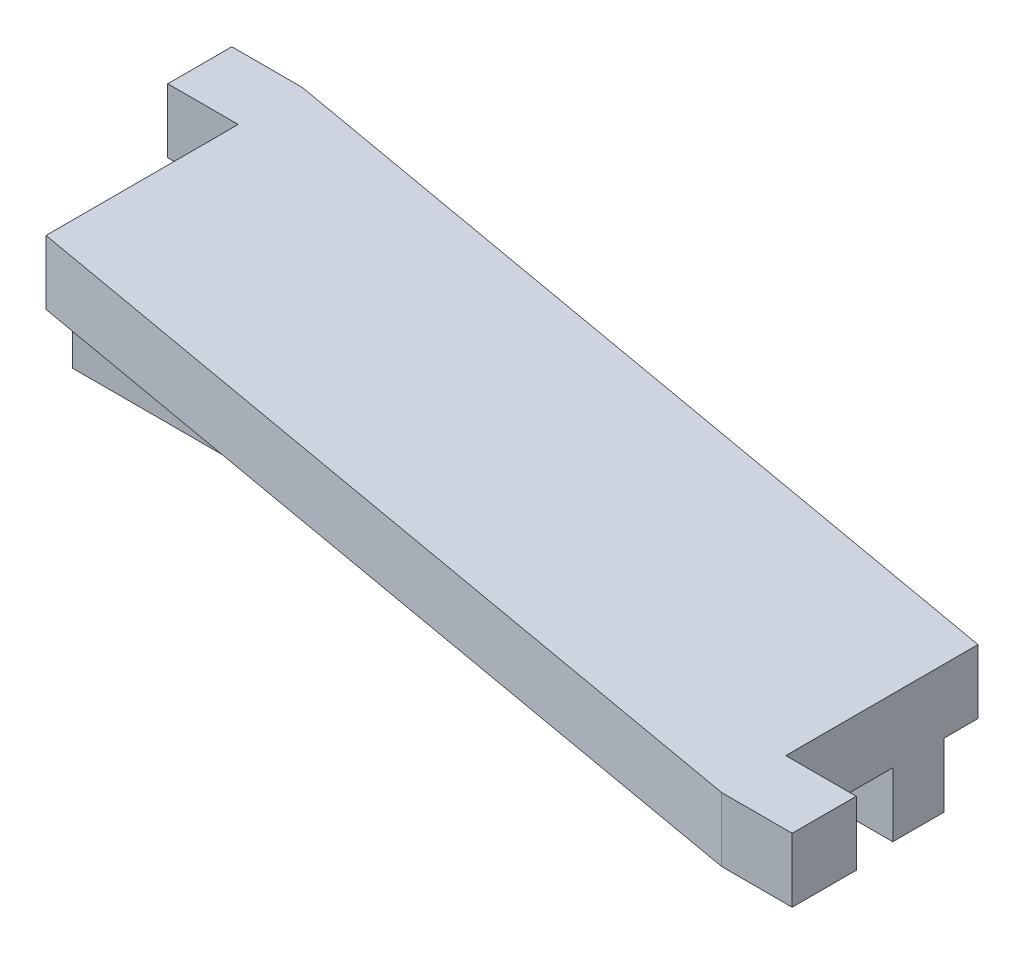
SolidWorks part; units mm, degrees
ref_plane "Front Plane" through (0, 0, 0) normal (0, 0, 1) x (1, 0, 0)
ref_plane "Top Plane" through (0, 0, 0) normal (0, 1, 0) x (1, 0, 0)
ref_plane "Right Plane" through (0, 0, 0) normal (1, 0, 0) x (0, 0, -1)
sketch "Sketch1" plane through (0, 0, 0) normal (0, 1, 0) x (1, 0, 0)
  line L0 (0, 0) -> (-128.025, 22.5743)
  line L1 (0, 0) -> (-98.5093, 0) construction
  line L2 (-128.025, 22.5743) -> (-128.025, 52.5743)
  line L3 (-128.025, 52.5743) -> (-139.025, 52.5743)
  line L4 (-139.025, 52.5743) -> (-139.025, 62.5743)
  line L5 (-139.025, 62.5743) -> (-128.025, 62.5743)
  line L6 (0, 40) -> (0, 10)
  line L7 (0, 10) -> (11, 10)
  line L8 (11, 10) -> (11, 0)
  line L9 (11, 0) -> (0, 0)
  line L10 (-128.025, 62.5743) -> (0, 40)
  dimension "D1" = 10
  dimension "D2" = 130
  dimension "D3" = 10
  dimension "D4" = 30
  dimension "D5" = 11
  dimension "D6" = 11
extrude "Boss-Extrude1" add sketch "Sketch1" along normal blind 10
sketch "Sketch2" plane through (0, 0, 0) normal (0, -1, 0) x (1, 0, 0)
  line L0 (0, -40) -> (-128.025, -37.5743)
  line L1 (-128.025, -52.5743) -> (-128.025, -22.5743) construction
  line L2 (-128.025, -37.5743) -> (-128.025, -32)
  line L3 (-128.025, -32) -> (0, -32)
  line L6 (0, -10) -> (0, -40) construction
  line L7 (0, -32) -> (0, -40)
  dimension "D1" = 8
extrude "Boss-Extrude2" [suppressed] add sketch "Sketch2" along normal blind 10
sketch "Sketch5" plane through (0, 10, 0) normal (0, 1, 0) x (1, 0, 0)
  line L0 (8.5, 10) -> (6.4527, 4.375)
  line L1 (11, 10) -> (0, 10) construction
  line L2 (6.4527, 4.375) -> (4.2785, 4.375)
  line L3 (4.2785, 4.375) -> (2.2311, 10)
  line L4 (6.4527, 4.375) -> (6.4527, 23.9951) construction
  line L5 (3.1411, 7.5) -> (7.5901, 7.5) construction
  line L6 (0, 0) -> (11, 0) construction
  line L7 (2.2311, 10) -> (8.5, 10)
  line L8 (-5.5377, 10) -> (0.7311, 10)
  line L9 (0.7311, 10) -> (-1.3162, 4.375)
  line L10 (-1.3162, 4.375) -> (-3.4904, 4.375)
  line L11 (-3.4904, 4.375) -> (-5.5377, 10)
  line L12 (-13.3066, 10) -> (-7.0377, 10)
  line L13 (-7.0377, 10) -> (-9.085, 4.375)
  line L14 (-9.085, 4.375) -> (-11.2592, 4.375)
  line L15 (-11.2592, 4.375) -> (-13.3066, 10)
  line L16 (-21.0754, 10) -> (-14.8066, 10)
  line L17 (-14.8066, 10) -> (-16.8539, 4.375)
  line L18 (-16.8539, 4.375) -> (-19.0281, 4.375)
  line L19 (-19.0281, 4.375) -> (-21.0754, 10)
  line L20 (-28.8443, 10) -> (-22.5754, 10)
  line L21 (-22.5754, 10) -> (-24.6227, 4.375)
  line L22 (-24.6227, 4.375) -> (-26.7969, 4.375)
  line L23 (-26.7969, 4.375) -> (-28.8443, 10)
  line L24 (-36.6131, 10) -> (-30.3443, 10)
  line L25 (-30.3443, 10) -> (-32.3916, 4.375)
  line L26 (-32.3916, 4.375) -> (-34.5658, 4.375)
  line L27 (-34.5658, 4.375) -> (-36.6131, 10)
  line L28 (-44.382, 10) -> (-38.1131, 10)
  line L29 (-38.1131, 10) -> (-40.1604, 4.375)
  line L30 (-40.1604, 4.375) -> (-42.3346, 4.375)
  line L31 (-42.3346, 4.375) -> (-44.382, 10)
  line L32 (-52.1508, 10) -> (-45.882, 10)
  line L33 (-45.882, 10) -> (-47.9293, 4.375)
  line L34 (-47.9293, 4.375) -> (-50.1035, 4.375)
  line L35 (-50.1035, 4.375) -> (-52.1508, 10)
  line L36 (-59.9197, 10) -> (-53.6508, 10)
  line L37 (-53.6508, 10) -> (-55.6981, 4.375)
  line L38 (-55.6981, 4.375) -> (-57.8723, 4.375)
  line L39 (-57.8723, 4.375) -> (-59.9197, 10)
  line L40 (-67.6885, 10) -> (-61.4197, 10)
  line L41 (-61.4197, 10) -> (-63.467, 4.375)
  line L42 (-63.467, 4.375) -> (-65.6412, 4.375)
  line L43 (-65.6412, 4.375) -> (-67.6885, 10)
  line L44 (-75.4574, 10) -> (-69.1885, 10)
  line L45 (-69.1885, 10) -> (-71.2358, 4.375)
  line L46 (-71.2358, 4.375) -> (-73.41, 4.375)
  line L47 (-73.41, 4.375) -> (-75.4574, 10)
  line L48 (-83.2262, 10) -> (-76.9574, 10)
  line L49 (-76.9574, 10) -> (-79.0047, 4.375)
  line L50 (-79.0047, 4.375) -> (-81.1789, 4.375)
  line L51 (-81.1789, 4.375) -> (-83.2262, 10)
  line L52 (-136.525, 52.5743) -> (-134.4777, 58.1993)
  line L53 (-139.025, 52.5743) -> (-128.025, 52.5743) construction
  line L54 (-134.4777, 58.1993) -> (-132.3035, 58.1993)
  line L55 (-132.3035, 58.1993) -> (-130.2562, 52.5743)
  line L56 (-134.4777, 58.1993) -> (-134.4777, 27.7415) construction
  line L57 (-135.6151, 55.0743) -> (-131.1661, 55.0743) construction
  line L58 (-128.025, 62.5743) -> (-139.025, 62.5743) construction
  line L59 (-136.525, 52.5743) -> (-130.2562, 52.5743)
  dimension "D1" = 20
  dimension "D2" = 3.125
  dimension "D3" = 7.5
  dimension "D4" = 4.449
  dimension "D5" = 2.5
  dimension "D6" = 12
  dimension "D7" = 20
  dimension "D8" = 7.5
  dimension "D9" = 3.125
  dimension "D10" = 4.449
  dimension "D11" = 2.5
  dimension "D12" = 1.5
extrude "Cut-Extrude3" [suppressed] cut sketch "Sketch5" against normal blind 10
sketch "Sketch6" plane through (0, 0, 0) normal (0, -1, 0) x (1, 0, 0)
  line L0 (0, -34.7) -> (-128.025, -34.7)
  line L1 (0, -10) -> (0, -40) construction
  line L2 (-128.025, -52.5743) -> (-128.025, -22.5743) construction
  line L3 (-128.025, -34.7) -> (-128.025, -26.7)
  line L4 (0, -34.7) -> (0, -26.7)
  line L5 (0, -26.7) -> (-128.025, -26.7)
  dimension "D1" = 5.3
  dimension "D2" = 8
extrude "Boss-Extrude3" add sketch "Sketch6" along normal blind 10
